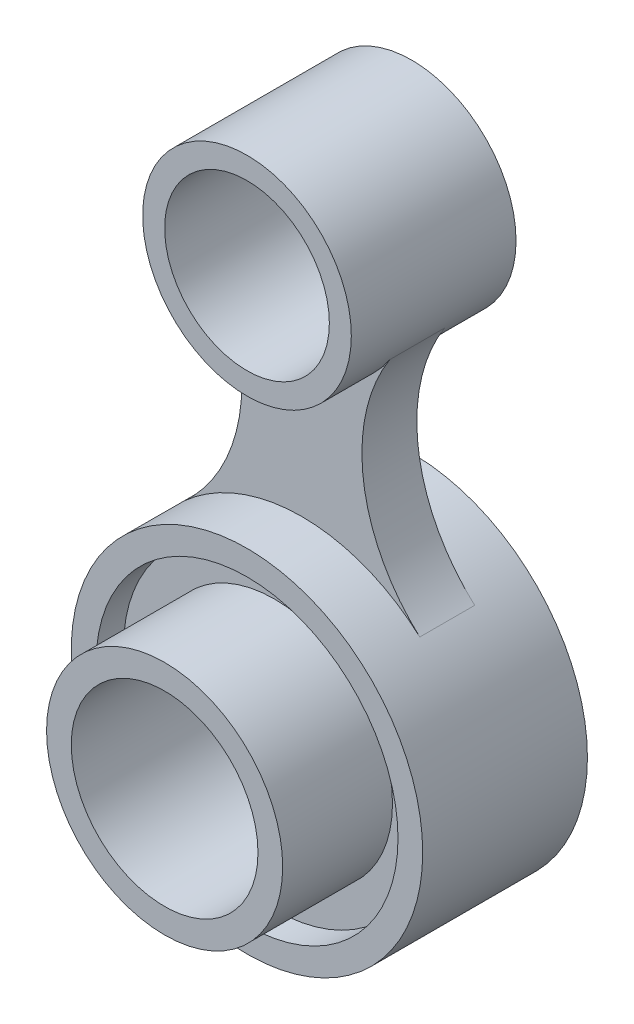
SolidWorks part; units mm, degrees
ref_plane "Front Plane" through (0, 0, 0) normal (0, 0, 1) x (1, 0, 0)
ref_plane "Top Plane" through (0, 0, 0) normal (0, 1, 0) x (1, 0, 0)
ref_plane "Right Plane" through (0, 0, 0) normal (1, 0, 0) x (0, 0, -1)
sketch "Sketch1" plane through (0, 0, 0) normal (0, 0, 1) x (1, 0, 0)
  circle A0 centre (0, 0) radius 32
  point P3 (0, 0)
  dimension "D1" = 64
extrude "Boss-Extrude3" add sketch "Sketch1" along normal blind 45
sketch "Sketch4" plane through (0, 0, 45) normal (0, 0, 1) x (1, 0, 0)
  circle A0 centre (0, 0) radius 17
  dimension "D1" = 34
extrude "Cut-Extrude1" cut sketch "Sketch4" against normal blind 45
sketch "Sketch5" plane through (0, 0, 45) normal (0, 0, 1) x (1, 0, 0)
  circle A0 centre (0, 0) radius 32
  circle A1 centre (0, 0) radius 21.5
  dimension "D1" = 64
  dimension "D2" = 43
extrude "Cut-Extrude2" cut sketch "Sketch5" against normal blind 15
sketch "Sketch6" plane through (0, 0, 30) normal (0, 0, 1) x (1, 0, 0)
  circle A0 centre (0, 0) radius 27.5
  circle A1 centre (0, 0) radius 21.5
  dimension "D1" = 55
  dimension "D2" = 43
extrude "Cut-Extrude3" cut sketch "Sketch6" against normal blind 5
sketch "Sketch7" plane through (0, 0, 0) normal (0, 0, 1) x (1, 0, 0)
  line L0 (0, 75) -> (0, -49925) construction
  line L1 (0, 75) -> (-50000, 75) construction
  line L2 (0, 0) -> (-50000, 0) construction
  circle A0 centre (0, 75) radius 15
  circle A1 centre (0, 75) radius 19
  dimension "D1" = 38
  dimension "D2" = 30
  dimension "D3" = 75
extrude "Boss-Extrude4" add sketch "Sketch7" along normal blind 30 separate body
sketch "Sketch8" plane through (0, 0, 0) normal (0, 0, 1) x (1, 0, 0)
  line L0 (0, 0) -> (0, 50000) construction
  arc A0 (15.9932, 64.7425) -> (21.4646, 23.7333) centre (42.9292, 47.4667) ccw
  circle A1 centre (0, 75) radius 19 construction
  circle A2 centre (0, 0) radius 32 construction
  arc A3 (-15.9932, 64.7425) -> (-21.4646, 23.7333) centre (-42.9292, 47.4667) cw
  arc A4 (21.4646, 23.7333) -> (-21.4646, 23.7333) centre (0, 0) ccw
  arc A5 (-15.9932, 64.7425) -> (15.9932, 64.7425) centre (0, 75) ccw
  dimension "D1" = 64
  dimension "D2" = 64
  dimension "D3" = 38
extrude "Boss-Extrude5" add sketch "Sketch8" along normal blind 10 from offset 10
